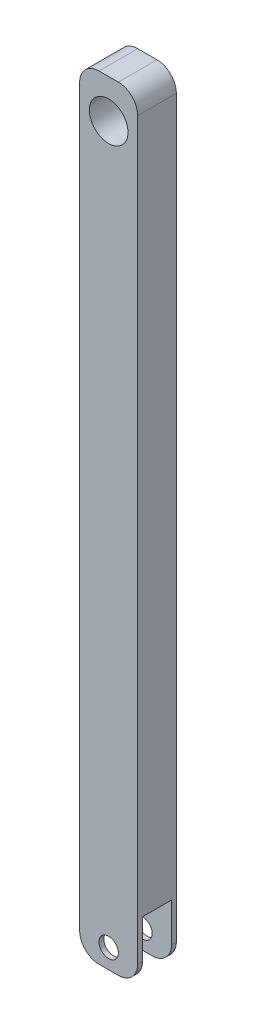
SolidWorks part; units mm, degrees
ref_plane "Front Plane" through (0, 0, 0) normal (0, 0, 1) x (1, 0, 0)
ref_plane "Top Plane" through (0, 0, 0) normal (0, 1, 0) x (1, 0, 0)
ref_plane "Right Plane" through (0, 0, 0) normal (1, 0, 0) x (0, 0, -1)
sketch "Sketch1" plane through (0, 0, 0) normal (0, 1, 0) x (1, 0, 0)
  line L0 (0, 0) -> (76.2, 0)
  line L1 (76.2, 0) -> (76.2, -50.8)
  line L2 (76.2, -50.8) -> (0, -50.8)
  line L3 (0, -50.8) -> (0, 0)
extrude "Boss-Extrude2" add sketch "Sketch1" along normal blind 1016
sketch "Sketch2" plane through (0, 0, 50.8) normal (0, 0, 1) x (1, 0, 0)
  line L0 (38.1, 1016) -> (38.1, 965.2)
  line L1 (0, 1016) -> (76.2, 1016) construction
  circle A0 centre (38.1, 965.2) radius 25.4
extrude "Cut-Extrude1" cut sketch "Sketch2" against normal blind 1016
fillet "Fillet1" radius 25.4 2 edges at (76.2, 1016, 25.4) (0, 1016, 25.4)
sketch "Sketch3" plane through (0, 0, 50.8) normal (0, 0, 1) x (1, 0, 0)
  line L0 (38.1, 0) -> (38.1, 25.4)
  line L1 (0, 0) -> (76.2, 0) construction
  circle A0 centre (38.1, 25.4) radius 12.7
extrude "Cut-Extrude2" cut sketch "Sketch3" against normal blind 254
sketch "Sketch4" plane through (0, 0, 0) normal (-1, 0, 0) x (0, 0, 1)
  line L0 (0, 0) -> (6.35, 0)
  line L1 (0, 0) -> (50.8, 0) construction
  line L2 (6.35, 0) -> (6.35, 50.8)
  line L3 (6.35, 50.8) -> (44.45, 50.8)
  line L4 (44.45, 50.8) -> (44.45, 0)
  line L5 (44.45, 0) -> (6.35, 0)
  line M4 (0, 0) -> (50.8, 0)
extrude "Cut-Extrude3" cut sketch "Sketch4" against normal blind 254 contours L4 L3 L2 M4
sketch "Sketch5" plane through (0, 0, 0) normal (-1, 0, 0) x (0, 0, 1)
  line L0 (6.35, 50.8) -> (6.35, 76.2)
  line L1 (6.35, 76.2) -> (44.45, 76.2)
  line L2 (44.45, 76.2) -> (44.45, 50.8)
  line L3 (44.45, 50.8) -> (6.35, 50.8)
extrude "Cut-Extrude4" cut sketch "Sketch5" against normal blind 254
fillet "Fillet2" radius 25.4 4 edges at (76.2, 0, 47.625) (0, 0, 47.625) (76.2, 0, 3.175) (0, 0, 3.175)
